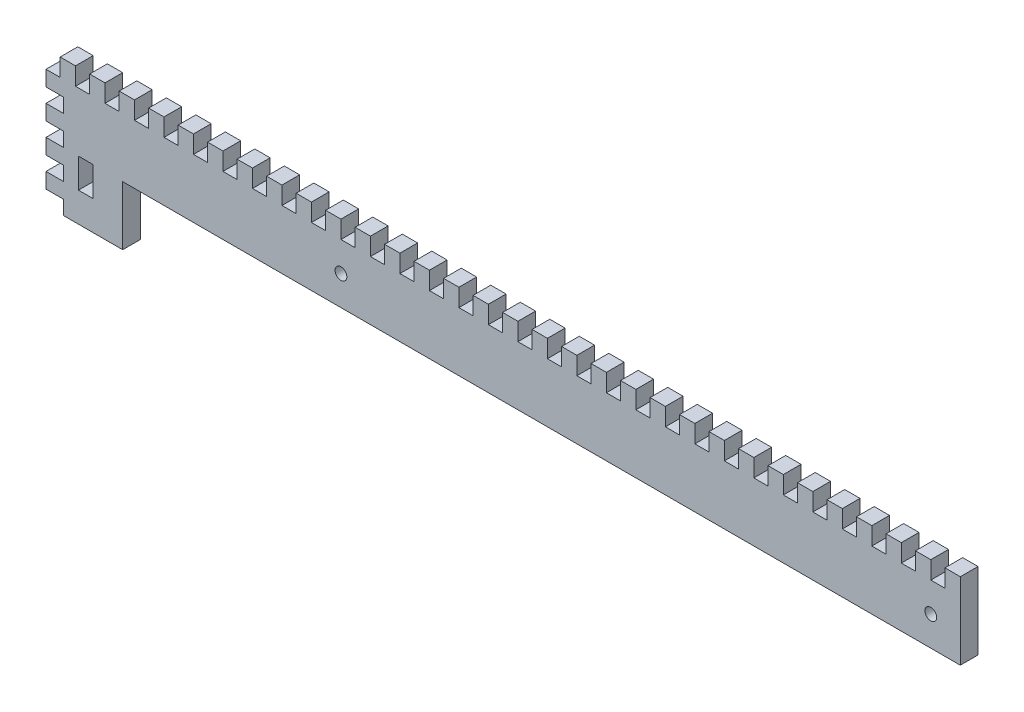
SolidWorks part; units mm, degrees
ref_plane "Plan de face" through (0, 0, 0) normal (0, 0, 1) x (1, 0, 0)
ref_plane "Plan de dessus" through (0, 0, 0) normal (0, 1, 0) x (1, 0, 0)
ref_plane "Plan de droite" through (0, 0, 0) normal (1, 0, 0) x (0, 0, -1)
sketch "Esquisse1" plane through (0, 0, 0) normal (0, 0, 1) x (1, 0, 0)
  line L0 (0, 0) -> (0, 26)
  line L1 (0, 26) -> (-5.2, 26)
  line L2 (-5.2, 26) -> (-5.2, 20)
  line L3 (-5.2, 20) -> (-10, 20)
  line L4 (-10, 20) -> (-10, 26)
  line L5 (-284, 0) -> (-337.7246, 0) construction
  line L6 (-10, 26) -> (-15.2, 26)
  line L7 (-15.2, 26) -> (-15.2, 20)
  line L8 (-15.2, 20) -> (-20, 20)
  line L9 (-20, 20) -> (-20, 26)
  line L10 (-20, 26) -> (-25.2, 26)
  line L11 (-25.2, 26) -> (-25.2, 20)
  line L12 (-25.2, 20) -> (-30, 20)
  line L13 (-30, 20) -> (-30, 26)
  line L14 (-30, 26) -> (-35.2, 26)
  line L15 (-35.2, 26) -> (-35.2, 20)
  line L16 (-35.2, 20) -> (-40, 20)
  line L17 (-40, 20) -> (-40, 26)
  line L18 (-40, 26) -> (-45.2, 26)
  line L19 (-45.2, 26) -> (-45.2, 20)
  line L20 (-45.2, 20) -> (-50, 20)
  line L21 (-50, 20) -> (-50, 26)
  line L22 (-50, 26) -> (-55.2, 26)
  line L23 (-55.2, 26) -> (-55.2, 20)
  line L24 (-55.2, 20) -> (-60, 20)
  line L25 (-60, 20) -> (-60, 26)
  line L26 (-60, 26) -> (-65.2, 26)
  line L27 (-65.2, 26) -> (-65.2, 20)
  line L28 (-65.2, 20) -> (-70, 20)
  line L29 (-70, 20) -> (-70, 26)
  line L30 (-70, 26) -> (-75.2, 26)
  line L31 (-75.2, 26) -> (-75.2, 20)
  line L32 (-75.2, 20) -> (-80, 20)
  line L33 (-80, 20) -> (-80, 26)
  line L34 (-80, 26) -> (-85.2, 26)
  line L35 (-85.2, 26) -> (-85.2, 20)
  line L36 (-85.2, 20) -> (-90, 20)
  line L37 (-90, 20) -> (-90, 26)
  line L38 (-90, 26) -> (-95.2, 26)
  line L39 (-95.2, 26) -> (-95.2, 20)
  line L40 (-95.2, 20) -> (-100, 20)
  line L41 (-100, 20) -> (-100, 26)
  line L42 (-100, 26) -> (-105.2, 26)
  line L43 (-105.2, 26) -> (-105.2, 20)
  line L44 (-105.2, 20) -> (-110, 20)
  line L45 (-110, 20) -> (-110, 26)
  line L46 (-110, 26) -> (-115.2, 26)
  line L47 (-115.2, 26) -> (-115.2, 20)
  line L48 (-115.2, 20) -> (-120, 20)
  line L49 (-120, 20) -> (-120, 26)
  line L50 (-120, 26) -> (-125.2, 26)
  line L51 (-125.2, 26) -> (-125.2, 20)
  line L52 (-125.2, 20) -> (-130, 20)
  line L53 (-130, 20) -> (-130, 26)
  line L54 (-130, 26) -> (-135.2, 26)
  line L55 (-135.2, 26) -> (-135.2, 20)
  line L56 (-135.2, 20) -> (-140, 20)
  line L57 (-140, 20) -> (-140, 26)
  line L58 (-140, 26) -> (-145.2, 26)
  line L59 (-145.2, 26) -> (-145.2, 20)
  line L60 (-145.2, 20) -> (-150, 20)
  line L61 (-150, 20) -> (-150, 26)
  line L62 (-150, 26) -> (-155.2, 26)
  line L63 (-155.2, 26) -> (-155.2, 20)
  line L64 (-155.2, 20) -> (-160, 20)
  line L65 (-160, 20) -> (-160, 26)
  line L66 (-160, 26) -> (-165.2, 26)
  line L67 (-165.2, 26) -> (-165.2, 20)
  line L68 (-165.2, 20) -> (-170, 20)
  line L69 (-170, 20) -> (-170, 26)
  line L70 (-170, 26) -> (-175.2, 26)
  line L71 (-175.2, 26) -> (-175.2, 20)
  line L72 (-175.2, 20) -> (-180, 20)
  line L73 (-180, 20) -> (-180, 26)
  line L74 (-180, 26) -> (-185.2, 26)
  line L75 (-185.2, 26) -> (-185.2, 20)
  line L76 (-185.2, 20) -> (-190, 20)
  line L77 (-190, 20) -> (-190, 26)
  line L78 (-190, 26) -> (-195.2, 26)
  line L79 (-195.2, 26) -> (-195.2, 20)
  line L80 (-195.2, 20) -> (-200, 20)
  line L81 (-200, 20) -> (-200, 26)
  line L82 (-200, 26) -> (-205.2, 26)
  line L83 (-205.2, 26) -> (-205.2, 20)
  line L84 (-205.2, 20) -> (-210, 20)
  line L85 (-210, 20) -> (-210, 26)
  line L86 (-210, 26) -> (-215.2, 26)
  line L87 (-215.2, 26) -> (-215.2, 20)
  line L88 (-215.2, 20) -> (-220, 20)
  line L89 (-220, 20) -> (-220, 26)
  line L90 (-220, 26) -> (-225.2, 26)
  line L91 (-225.2, 26) -> (-225.2, 20)
  line L92 (-225.2, 20) -> (-230, 20)
  line L93 (-230, 20) -> (-230, 26)
  line L94 (-230, 26) -> (-235.2, 26)
  line L95 (-235.2, 26) -> (-235.2, 20)
  line L96 (-235.2, 20) -> (-240, 20)
  line L97 (-240, 20) -> (-240, 26)
  line L98 (-240, 26) -> (-245.2, 26)
  line L99 (-245.2, 26) -> (-245.2, 20)
  line L102 (-250, 20) -> (-250, 26) [skipped]
  line L103 (-310, 14.8) -> (-304, 14.8)
  line L104 (-304, 14.8) -> (-304, 10)
  line L105 (-304, 10) -> (-310, 10)
  line L106 (-310, 10) -> (-310, 4.8)
  line L107 (-310, 4.8) -> (-304, 4.8)
  line L108 (-304, 4.8) -> (-304, 0)
  line L109 (-304, 0) -> (-310, 0)
  line L110 (-310, 0) -> (-310, -5.2)
  line L111 (-310, -5.2) -> (-304, -5.2)
  line L112 (-304, -5.2) -> (-304, -10)
  line L113 (-304, -10) -> (-310, -10)
  line L114 (-310, -10) -> (-310, -15.2)
  line L115 (-310, -15.2) -> (-304, -15.2)
  line L116 (-304, -15.2) -> (-304, -20)
  line L117 (-304, -20) -> (-284, -20)
  line L118 (-304, -20) -> (-310, -20) [skipped]
  line L119 (-284, -20) -> (-284, 0)
  line L121 (-10, 20) -> (-305.2, 20) construction
  line L122 (-299, 0) -> (-294, 0)
  line L123 (-299, 0) -> (-299, -10)
  line L124 (-299, -10) -> (-294, -10)
  line L125 (-294, 0) -> (-294, -10)
  line L126 (-245.2, 20) -> (-250, 20) [skipped]
  line L127 (-245.2, 20) -> (-250, 20)
  line L128 (-250, 20) -> (-250, 26)
  line L129 (-250, 26) -> (-255.2, 26)
  line L130 (-255.2, 26) -> (-255.2, 20)
  line L131 (-255.2, 20) -> (-260, 20)
  line L132 (-260, 20) -> (-260, 26)
  line L133 (-260, 26) -> (-265.2, 26)
  line L134 (-265.2, 26) -> (-265.2, 20)
  line L135 (-265.2, 20) -> (-270, 20)
  line L136 (-270, 20) -> (-270, 26)
  line L137 (-270, 26) -> (-275.2, 26)
  line L138 (-275.2, 26) -> (-275.2, 20)
  line L139 (-275.2, 20) -> (-280, 20)
  line L140 (-280, 20) -> (-280, 26)
  line L141 (-280, 26) -> (-285.2, 26)
  line L142 (-285.2, 26) -> (-285.2, 20)
  line L143 (-285.2, 20) -> (-290, 20)
  line L144 (-290, 20) -> (-290, 26)
  line L145 (-290, 26) -> (-295.2, 26)
  line L146 (-295.2, 26) -> (-295.2, 20)
  line L147 (-295.2, 20) -> (-300, 20)
  line L148 (-300, 20) -> (-300, 26)
  line L149 (-300, 26) -> (-305.2, 26)
  line L150 (-305.2, 26) -> (-305.2, 20)
  line L152 (-284, 0) -> (0, 0)
  line L154 (-305.2, 20) -> (-310, 20)
  line L155 (-315.2, 26) -> (-315.2, 20) [skipped]
  line L156 (-310, 26) -> (-315.2, 26) [skipped]
  line L157 (-310, 20) -> (-310, 26) [skipped]
  line L158 (-305.2, 20) -> (-310, 20) [skipped]
  line L159 (-310, 20) -> (-310, 14.8)
  circle A0 centre (-210, 10) radius 2
  circle A1 centre (-10, 10) radius 2
  dimension "D11" = 4
  dimension "D12" = 4
  dimension "D13" = 200
  dimension "D14" = 10
  dimension "D15" = 4.8
  dimension "D1" = 26
  dimension "D2" = 5.2
  dimension "D3" = 4.8
  dimension "D4" = 6
  dimension "D5" = 6
  dimension "D7" = 20
  dimension "D8" = 4.8
  dimension "D9" = 5.2
  dimension "D16" = 5
  dimension "D17" = 10
  dimension "D18" = 10
  dimension "D19" = 5
  dimension "D21" = 10
  dimension "D22" = 5.2
  dimension "D23" = 20
  dimension "D6" = 25
  dimension "D10" = 4
  dimension "D20" = 8
extrude "Boss.-Extru.1" add sketch "Esquisse1" along normal blind 6
